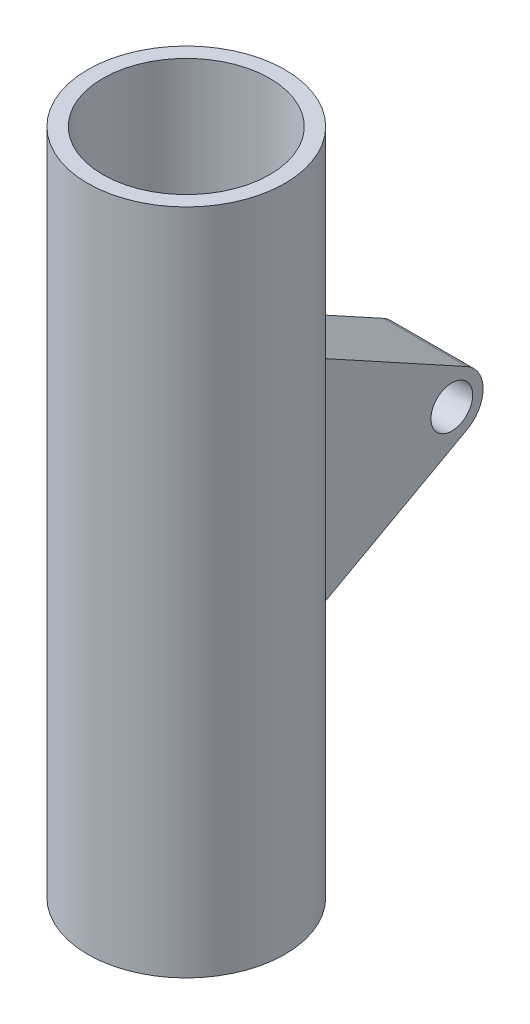
SolidWorks part; units mm, degrees
ref_plane "Front Plane" through (0, 0, 0) normal (0, 0, 1) x (1, 0, 0)
ref_plane "Top Plane" through (0, 0, 0) normal (0, 1, 0) x (1, 0, 0)
ref_plane "Right Plane" through (0, 0, 0) normal (1, 0, 0) x (0, 0, -1)
sketch "Sketch1" plane through (0, 0, 0) normal (0, 1, 0) x (1, 0, 0)
  circle A0 centre (0, 0) radius 25.4
  circle A1 centre (0, 0) radius 30
  dimension "D1" = 50.8
  dimension "D2" = 60
extrude "Boss-Extrude1" add sketch "Sketch1" along normal blind 203.2
ref_plane "Plane1" through (0, 0, -30) normal (0, 0, -1) x (-1, 0, 0)
sketch "Sketch2" plane through (0, 0, -30) normal (0, 0, -1) x (-1, 0, 0)
  line L0 (-12.7, 69.85) -> (-12.7, 133.35)
  line L1 (-12.7, 69.85) -> (12.7, 69.85)
  line L2 (-12.7, 133.35) -> (12.7, 133.35)
  line L3 (12.7, 69.85) -> (12.7, 133.35)
  line L4 (-12.7, 69.85) -> (12.7, 133.35) construction
  line L5 (-12.7, 133.35) -> (12.7, 69.85) construction
  line L6 (0, 203.2) -> (0, 0) construction
  line L7 (25.4, 203.2) -> (-25.4, 203.2) construction
  line L8 (30, 203.2) -> (30, 0)
  line L9 (30, 203.2) -> (30, 0) construction
  line L10 (30, 0) -> (-30, 0)
  line L11 (30, 0) -> (-30, 0) construction
  line L12 (-30, 0) -> (-30, 203.2)
  line L13 (-30, 0) -> (-30, 203.2) construction
  line L14 (-30, 203.2) -> (30, 203.2)
  line L15 (-30, 203.2) -> (30, 203.2) construction
  point P1 (0, 101.6)
  point P14 (0, 138.4974)
  point P15 (0, 0)
  point P16 (0, 172.1771)
  point P17 (0, 101.6)
  dimension "D1" = 63.5
  dimension "D2" = 25.4
extrude "Boss-Extrude2" add sketch "Sketch2" along normal blind 50.8 and the other way up to next
sketch "Sketch3" plane through (12.7, 0, 0) normal (1, 0, 0) x (0, 0, -1)
  line L0 (-30, 0) -> (-30, 203.2)
  line L1 (-30, 0) -> (-30, 203.2) construction
  line L2 (-30, 203.2) -> (30, 203.2)
  line L3 (-30, 203.2) -> (30, 203.2) construction
  line L4 (30, 203.2) -> (30, 133.35)
  line L5 (30, 203.2) -> (30, 133.35) construction
  line L6 (30, 133.35) -> (80.8, 133.35)
  line L7 (30, 133.35) -> (80.8, 133.35) construction
  line L8 (80.8, 133.35) -> (80.8, 69.85)
  line L9 (80.8, 133.35) -> (80.8, 69.85) construction
  line L10 (80.8, 69.85) -> (30, 69.85)
  line L11 (80.8, 69.85) -> (30, 69.85) construction
  line L12 (30, 69.85) -> (30, 0)
  line L13 (30, 69.85) -> (30, 0) construction
  line L14 (30, 0) -> (-30, 0)
  line L15 (30, 0) -> (-30, 0) construction
  line L16 (30, 133.35) -> (72.6789, 109.9522)
  line L17 (30, 69.85) -> (72.6789, 93.2478)
  line L18 (30, 133.35) -> (30, 69.85)
  circle A0 centre (68.1, 101.6) radius 6.35
  circle A1 centre (68.1, 101.6) radius 9.525
  point P8 (30, 69.85)
  point P11 (71.1464, 92.5753)
  point P12 (80.8, 101.6)
  line M10 (80.8, 133.35) -> (27.1792, 133.35)
  line M12 (27.1792, 69.85) -> (80.8, 69.85)
  line M13 (80.8, 69.85) -> (80.8, 133.35)
  dimension "D2" = 12.7
  dimension "D3" = 19.05
  dimension "D1" = 12.7
extrude "Cut-Extrude3" cut sketch "Sketch3" against normal up to next and the other way through all contours A1 L17 L16 M12 M13 M10 | A0
